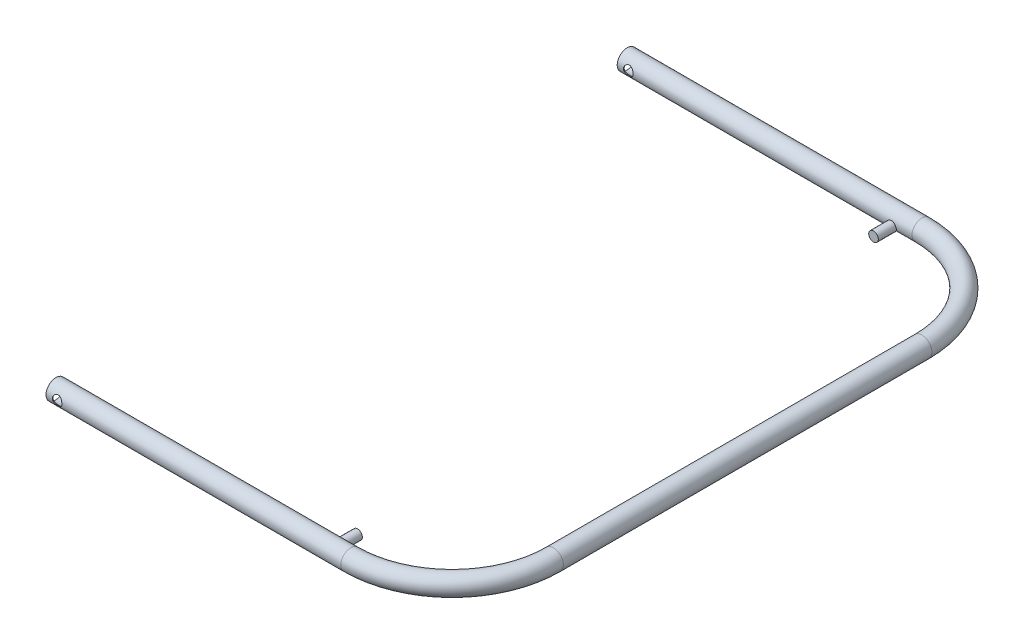
SolidWorks part; units mm, degrees
ref_plane "Front Plane" through (0, 0, 0) normal (0, 0, 1) x (1, 0, 0)
ref_plane "Top Plane" through (0, 0, 0) normal (0, 1, 0) x (1, 0, 0)
ref_plane "Right Plane" through (0, 0, 0) normal (1, 0, 0) x (0, 0, -1)
sketch "Sketch1" plane through (0, 0, 0) normal (0, 1, 0) x (1, 0, 0)
  line L0 (0, 400) -> (400, 400)
  line L1 (550, 250) -> (550, -250)
  line L2 (400, -400) -> (0, -400)
  line L3 (-768.8564, 0) -> (914.8418, 0) construction
  arc A0 (550, -250) -> (400, -400) centre (400, -250) cw
  arc A1 (400, 400) -> (550, 250) centre (400, 250) cw
  point P12 (550, -400)
  point P15 (550, 400)
  dimension "D3" = 150
  dimension "D1" = 800
  dimension "D2" = 550
ref_plane "Plane1" through (0, 0, -400) normal (1, 0, 0) x (0, 0, -1)
sketch "Sketch2" plane through (0, 0, -400) normal (1, 0, 0) x (0, 0, -1)
  line L0 (0, 0) -> (-150, 0) construction
  circle A0 centre (-12.5, 0) radius 12.5
  dimension "D1" = 25
sweep "Sweep-Thin1" add profiles "Sketch2" path "Sketch1" parameters "D1"=1
ref_plane "Plane2" through (0, 12.5, 0) normal (0, 1, 0) x (1, 0, 0)
sketch "Sketch10" plane through (0, 12.5, 0) normal (0, 1, 0) x (1, 0, 0)
  line L0 (45, 387.5) -> (45, -387.5)
  line L1 (45, -387.5) -> (400, -387.5)
  line L2 (400, -401) -> (400, -374) construction
  line L3 (400, -387.5) -> (537.5, -250)
  line L4 (524, -250) -> (551, -250) construction
  line L5 (537.5, -250) -> (537.5, 250)
  line L6 (551, 250) -> (524, 250) construction
  line L7 (537.5, 250) -> (400, 387.5)
  line L8 (400, 374) -> (400, 401) construction
  line L9 (400, 387.5) -> (45, 387.5)
  line L10 (0, -375) -> (0, -400) construction
  dimension "D1" = 45
sketch "Sketch11" plane through (0, 0, 0) normal (0, 0, 1) x (1, 0, 0)
  line L0 (0, 0) -> (400, 0) construction
  line L1 (400, 13.5) -> (400, -13.5) construction
  circle A0 centre (15, 0) radius 6.5
  dimension "D1" = 13
  dimension "D2" = 15
extrude "Cut-Extrude1" cut sketch "Sketch11" against normal mid plane 1033 contours A0
ref_plane "Plane3" through (0, 0, -350) normal (0, 0, 1) x (1, 0, 0)
sketch "Sketch12" plane through (0, 0, -350) normal (0, 0, 1) x (1, 0, 0)
  line L0 (371.7556, 14) -> (371.7556, -13.5) construction
  line L1 (239, 14) -> (396, 14) construction
  line L2 (0, -13.5) -> (400, -13.5) construction
  circle A0 centre (371.7556, -3.6135) radius 6.5
  dimension "D1" = 13
extrude "Boss-Extrude1" add sketch "Sketch12" against normal up to surface (24.4926 mm away)
ref_plane "Plane4" through (0, 0, 350) normal (0, 0, 1) x (1, 0, 0)
sketch "Sketch13" plane through (0, 0, 350) normal (0, 0, 1) x (1, 0, 0)
  circle A0 centre (371.7556, -3.6135) radius 6.5 construction
  circle A1 centre (371.7556, -3.6135) radius 6.5
extrude "Boss-Extrude2" add sketch "Sketch13" along normal up to next
sketch "Bend-Lines1" [suppressed] plane through (0, 0, 0) normal (0, 1, 0) x (1, 0, 0)
sketch "Bounding-Box1" [suppressed] plane through (0, 0, 0) normal (0, 1, 0) x (1, 0, 0)
